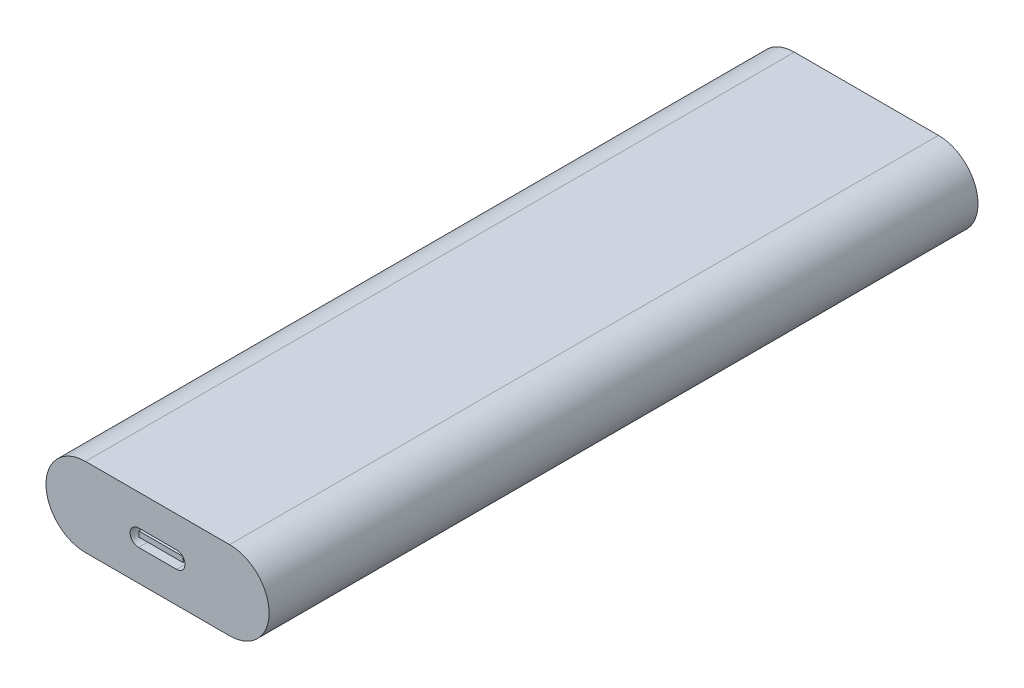
SolidWorks part; units mm, degrees
material "PET"
ref_plane "Front Plane" through (0, 0, 0) normal (0, 0, 1) x (1, 0, 0)
ref_plane "Top Plane" through (0, 0, 0) normal (0, 1, 0) x (1, 0, 0)
ref_plane "Right Plane" through (0, 0, 0) normal (1, 0, 0) x (0, 0, -1)
sketch "Sketch1" plane through (0, 0, 0) normal (0, 0, 1) x (1, 0, 0)
  line L0 (-10.95, 0) -> (10.95, 0) construction
  line L1 (-10.95, 6) -> (10.95, 6)
  line L2 (-10.95, -6) -> (10.95, -6)
  line L3 (-16.95, 0) -> (16.95, 0) construction
  arc A0 (-10.95, 6) -> (-10.95, -6) centre (-10.95, 0) ccw
  arc A1 (10.95, -6) -> (10.95, 6) centre (10.95, 0) ccw
  point P2 (0, 0)
  dimension "D1" = 33.9
  dimension "D2" = 12
extrude "Boss-Extrude1" add sketch "Sketch1" against normal blind 107.7
sketch "Sketch2" plane through (0, 0, 0) normal (0, 0, 1) x (1, 0, 0)
  line L0 (-2.89, 0) -> (2.89, 0) construction
  line L1 (-2.89, 1.28) -> (2.89, 1.28)
  line L2 (-2.89, -1.28) -> (2.89, -1.28)
  line L3 (-4.17, 0) -> (4.17, 0) construction
  arc A0 (-2.89, 1.28) -> (-2.89, -1.28) centre (-2.89, 0) ccw
  arc A1 (2.89, -1.28) -> (2.89, 1.28) centre (2.89, 0) ccw
  point P2 (0, 0)
  dimension "D1" = 8.34
  dimension "D2" = 2.56
extrude "Cut-Extrude1" cut sketch "Sketch2" against normal blind 6.5
sketch "Sketch3" plane through (0, 0, -6.5) normal (0, 0, 1) x (1, 0, 0)
  line L1 (-3.345, -0.4) -> (3.345, -0.4)
  line L2 (-3.345, -0.4) -> (-3.345, 0.4)
  line L3 (-3.345, 0.4) -> (3.345, 0.4)
  line L4 (3.345, -0.4) -> (3.345, 0.4)
  line L5 (-3.345, -0.4) -> (3.345, 0.4) construction
  line L6 (-3.345, 0.4) -> (3.345, -0.4) construction
  point P0 (0, 0)
  dimension "D1" = 6.69
  dimension "D2" = 0.8
extrude "Boss-Extrude2" add sketch "Sketch3" along normal offset from surface (6 mm away) 0.5 up to face at (0, 0, 0)
